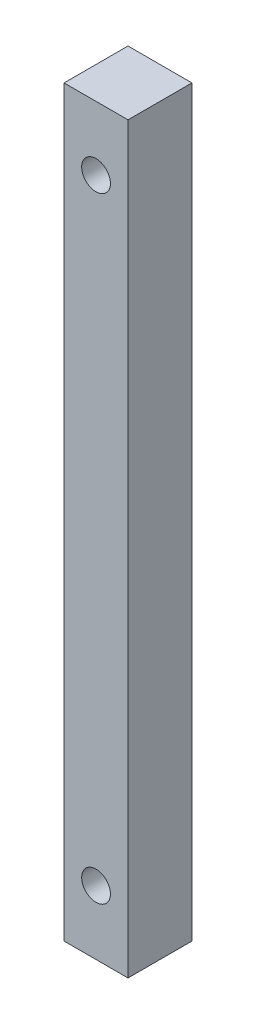
SolidWorks part; units mm, degrees
material "7075-T6, Plate (SS)"
ref_plane "Front Plane" through (0, 0, 0) normal (0, 0, 1) x (1, 0, 0)
ref_plane "Top Plane" through (0, 0, 0) normal (0, 1, 0) x (1, 0, 0)
ref_plane "Right Plane" through (0, 0, 0) normal (1, 0, 0) x (0, 0, -1)
sketch "Sketch1" plane through (0, 0, 0) normal (0, 0, 1) x (1, 0, 0)
  line L0 (2.54, 0) -> (2.54, -59.055) construction
  line L1 (0, 0) -> (5.08, 0)
  line L2 (0, 0) -> (0, -59.055)
  line L3 (0, -59.055) -> (5.08, -59.055)
  line L4 (5.08, 0) -> (5.08, -59.055)
  circle A0 centre (2.54, -5.08) radius 1.143
  circle A1 centre (2.54, -53.975) radius 1.143
  dimension "D1" = 5.08
  dimension "D3" = 2.286
  dimension "D5" = 2.286
  dimension "D6" = 48.895
  dimension "D2" = 5.08
  dimension "D4" = 5.08
extrude "Boss-Extrude1" add sketch "Sketch1" along normal blind 5.08
